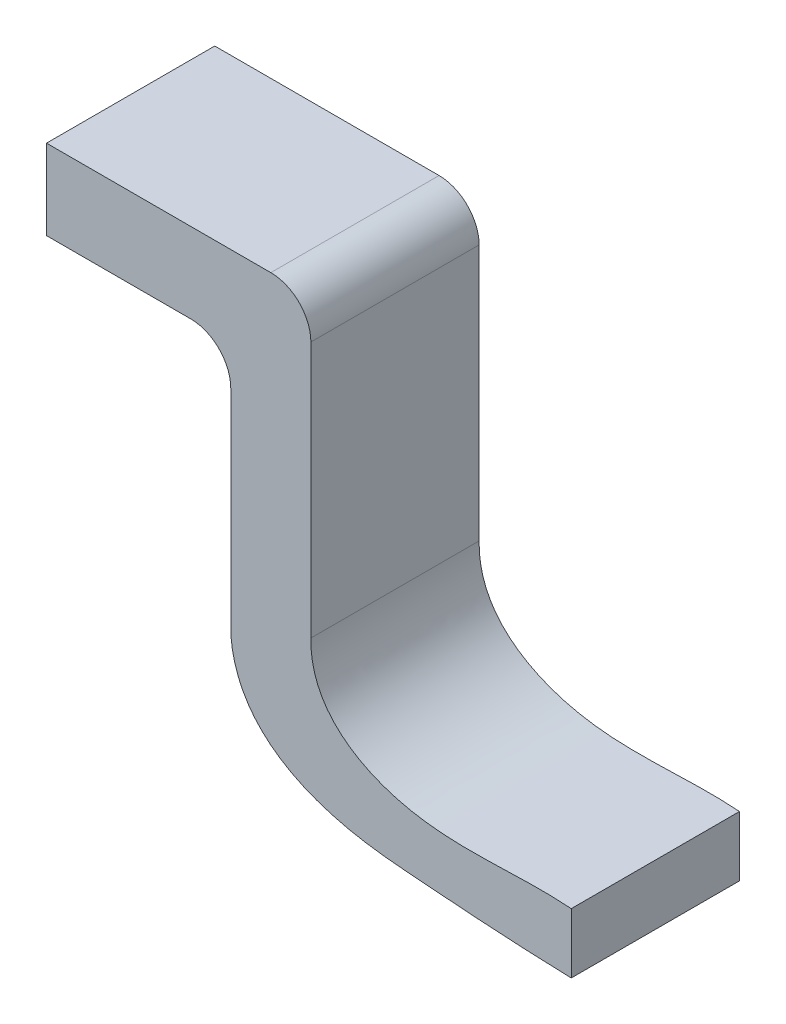
SolidWorks part; units mm, degrees
ref_plane "Front Plane" through (0, 0, 0) normal (0, 0, 1) x (1, 0, 0)
ref_plane "Top Plane" through (0, 0, 0) normal (0, 1, 0) x (1, 0, 0)
ref_plane "Right Plane" through (0, 0, 0) normal (1, 0, 0) x (0, 0, -1)
sketch "Sketch1" plane through (0, 0, 0) normal (0, 0, 1) x (1, 0, 0)
  line L2 (0, 0.15) -> (4.0487, 0.15) construction
  line L3 (0, 0.95) -> (0, 1.15)
  line L4 (1.31, 0.2) -> (1.31, 0)
  line L6 (0.66, 0.0721) -> (0.66, 1.05) construction
  line L7 (0, 1.15) -> (0, 0.95)
  line L8 (0, 0.95) -> (0, 1.15)
  line L9 (1.31, 0.15) -> (1.31, 0)
  line L10 (0, 0.95) -> (0.36, 0.95)
  line L11 (0.46, 0.85) -> (0.46, 0.3178)
  line L13 (1.31, 0) -> (1.31, 0.2)
  line L14 (0, 1.15) -> (0.56, 1.15)
  line L15 (0.66, 1.05) -> (0.66, 0.41)
  arc A0 (0.36, 0.95) -> (0.46, 0.85) centre (0.36, 0.85) cw
  arc A1 (0.66, 1.05) -> (0.56, 1.15) centre (0.56, 1.05) ccw
  spline S0 degree 3 poles (0.46, 0.3178) (0.4749, 0.1346) (0.691, 0.0442) (0.9476, 0.0191) (1.1924, 0.0028) (1.31, 0) knots 0 0 0 0 0.373087 0.499547 0.782662 0.782662 0.782662 0.782662
  spline S1 degree 3 poles (0.66, 0.41) (0.657, 0.2656) (0.9084, 0.1096) (1.171, 0.1606) (1.31, 0.15) knots 0 0 0 0 0.461377 1 1 1 1
  point P14 (0.7188, 0.2453)
  point P23 (0.66, 1.15)
  point P26 (0.46, 0.15)
  point P27 (0.8019, 0.2144)
  point P29 (0.66, 0.2144)
  point P30 (1.0676, 0.15)
  point P31 (1.0317, 0.1657)
  point P32 (0.6889, 0.3033)
  point P34 (0.9232, 0.1851)
  point P36 (0.7337, 0.241)
  point P37 (1.0572, 0.1636)
  point P38 (0.8914, 0.1657)
  point P41 (1.1487, 0.15)
  point P43 (0.9068, 0.0238)
  point P44 (0.7685, 0.0411)
  point P45 (1.1156, 0.15)
  dimension "D4" = 0.2
  dimension "D8" = 0.1
  dimension "D9" = 0.1
  dimension "D10" = 0.2
  dimension "D7" = 0.2
extrude "Boss-Extrude1" add sketch "Sketch1" along normal blind 0.42 contours S1 L15 A1 L14 L3 L10 A0 L11 S0 L4
